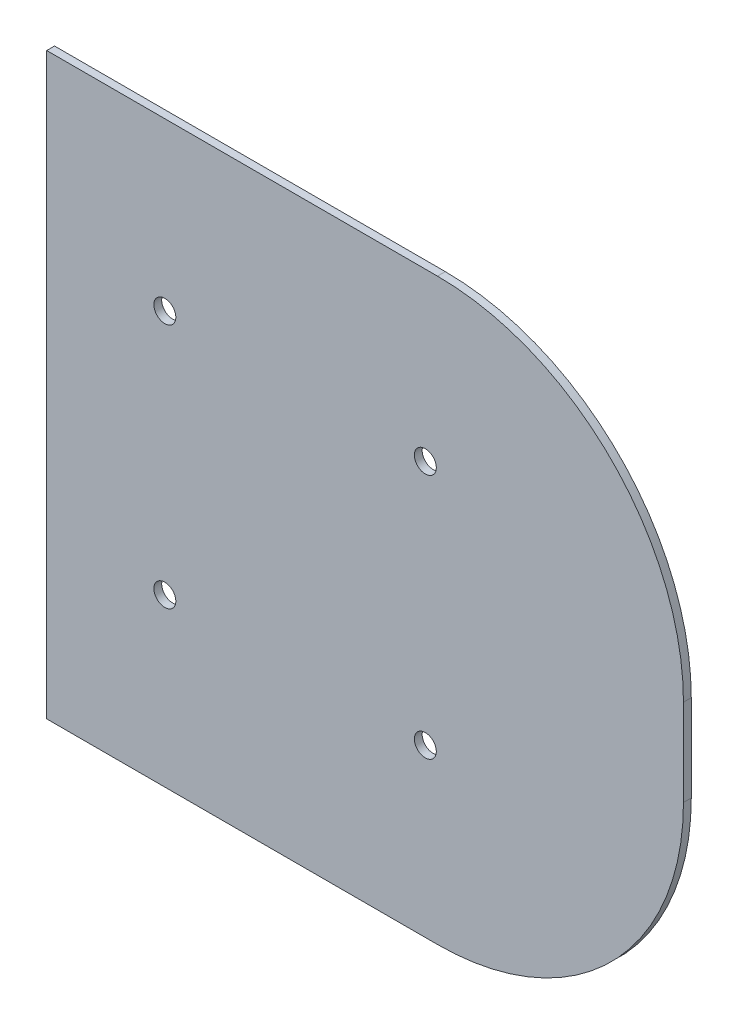
SolidWorks part; units mm, degrees
ref_plane "Ön Düzlem" through (0, 0, 0) normal (0, 0, 1) x (1, 0, 0)
ref_plane "Üst Düzlem" through (0, 0, 0) normal (0, 1, 0) x (1, 0, 0)
ref_plane "Sağ Düzlem" through (0, 0, 0) normal (1, 0, 0) x (0, 0, -1)
sketch "Çizim1" plane through (0, 0, 0) normal (0, 0, 1) x (1, 0, 0)
  line L1 (-110, -100) -> (25, -100)
  line L2 (-110, -100) -> (-110, 100)
  line L3 (-110, 100) -> (25, 100)
  line L4 (110, -15) -> (110, 15)
  line L5 (-110, -100) -> (110, 100) construction
  line L6 (-110, 100) -> (110, -100) construction
  arc A0 (25, 100) -> (110, 15) centre (25, 15) cw
  arc A1 (25, -100) -> (110, -15) centre (25, -15) ccw
  point P0 (0, 0)
  dimension "D3" = 85
  dimension "D4" = 85
  dimension "D1" = 200
  dimension "D2" = 220
extrude "Yükseklik-Ekstrüzyon3" add sketch "Çizim1" along normal blind 2.7
sketch "Çizim2" plane through (0, 0, 2.7) normal (0, 0, 1) x (1, 0, 0)
  line L0 (0, 0) -> (50000, 0) construction
  circle A0 centre (-69.1872, 42.4686) radius 3.79
  circle A1 centre (20.8128, 42.4686) radius 3.79
  circle A2 centre (20.8128, -42.4686) radius 3.79
  circle A3 centre (-69.1872, -42.4686) radius 3.79
  dimension "D1" = 2
  dimension "D2" = 7.58
extrude "Kes-Ekstrüzyon1" cut sketch "Çizim2" against normal blind 2.75
